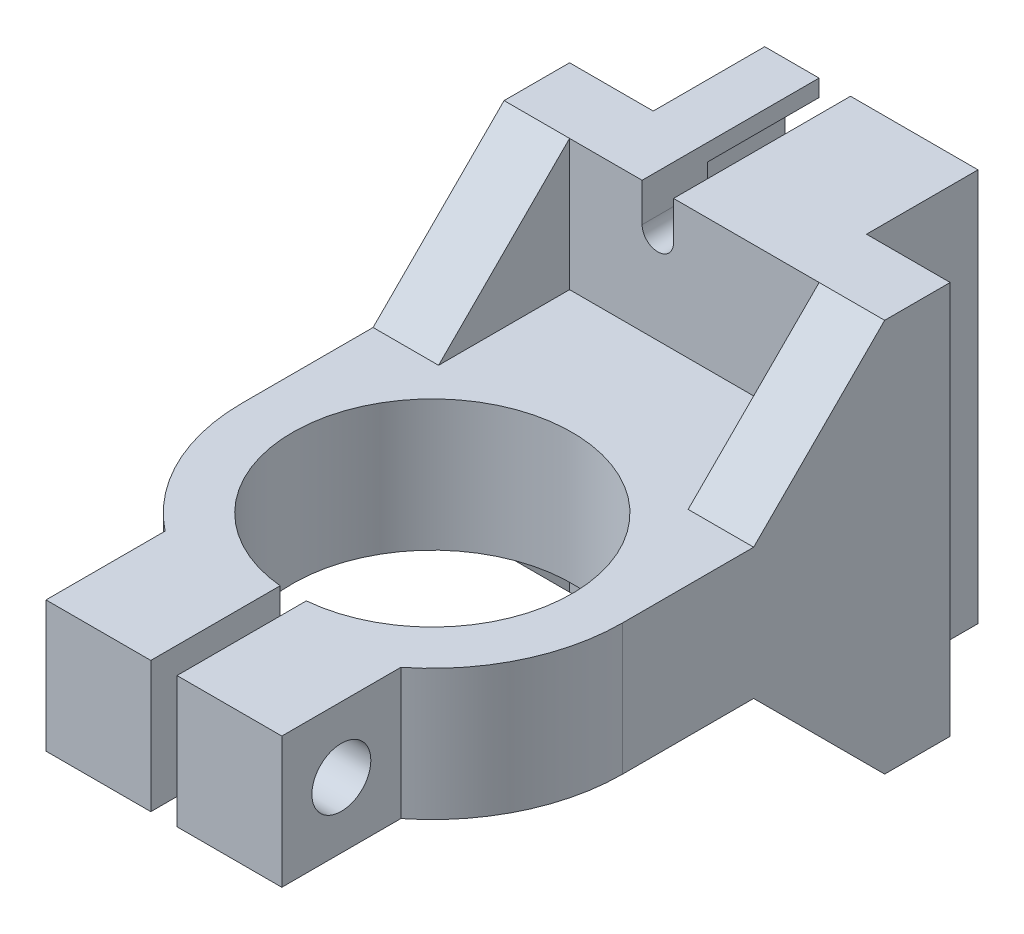
SolidWorks part; units mm, degrees
material "ABS"
ref_plane "Alzado" through (0, 0, 0) normal (0, 0, 1) x (1, 0, 0)
ref_plane "Planta" through (0, 0, 0) normal (0, 1, 0) x (1, 0, 0)
ref_plane "Vista lateral" through (0, 0, 0) normal (1, 0, 0) x (0, 0, -1)
sketch "Croquis1" plane through (0, 0, 0) normal (0, 1, 0) x (1, 0, 0)
  line L0 (0, 0) -> (0, -25) construction
  line L1 (14.525, 0) -> (-14.525, 0)
  line L2 (-14.525, 0) -> (-14.525, -10)
  line L3 (-14.525, -10) -> (-5, -10)
  line L4 (-5, -10) -> (-5, -11.3627)
  line L5 (14.525, 0) -> (14.525, -10)
  line L6 (14.525, -10) -> (5, -10)
  line L7 (5, -10) -> (5, -11.3627)
  arc A0 (-5, -11.3627) -> (5, -11.3627) centre (0, -25) ccw
  circle A1 centre (0, -25) radius 10.668
  point P7 (0, 0)
  dimension "D1" = 29.05
  dimension "D2" = 21.336
  dimension "D3" = 10
  dimension "D4" = 29.05
  dimension "D5" = 25
  dimension "D6" = 5
  dimension "D7" = 10
extrude "Saliente-Extruir1" add sketch "Croquis1" along normal mid plane 10
ref_plane "Plano1" through (0, 0, 39.525) normal (0, 0, 1) x (1, 0, 0)
sketch "Croquis7" plane through (0, 5, 0) normal (0, 1, 0) x (1, 0, 0)
  line L0 (0, -35.668) -> (0, -39.525) construction
  line L2 (1, -41.5965) -> (-1, -41.5965)
  line L3 (1, -41.5965) -> (1, -33.5965)
  line L4 (1, -33.5965) -> (-1, -33.5965)
  line L5 (-1, -41.5965) -> (-1, -33.5965)
  line L6 (1, -41.5965) -> (-1, -33.5965) construction
  line L7 (1, -33.5965) -> (-1, -41.5965) construction
  circle A0 centre (0, -25) radius 10.668 construction
  arc A1 (-5, -11.3627) -> (5, -11.3627) centre (0, -25) ccw construction
  point P7 (0, -37.5965)
  dimension "D1" = 2
  dimension "D2" = 8
extrude "Cortar-Extruir5" cut sketch "Croquis7" against normal through all
sketch "Croquis8" plane through (0, 5, 0) normal (0, 1, 0) x (1, 0, 0)
  line L0 (-1, -39.4905) -> (-1, -45.4905)
  line L1 (-1, -45.4905) -> (-9, -45.4905)
  line L2 (-9, -45.4905) -> (-9, -36.4007)
  line L3 (0, -16.5) -> (0, 16.5) construction
  line L4 (9, -45.4905) -> (9, -36.4007)
  line L5 (1, -45.4905) -> (9, -45.4905)
  line L6 (1, -39.4905) -> (1, -45.4905)
  arc A0 (-5, -11.3627) -> (-1, -39.4905) centre (0, -25) ccw construction
  arc A1 (-9, -36.4007) -> (-1, -39.4905) centre (0, -25) ccw
  arc A2 (9, -36.4007) -> (1, -39.4905) centre (0, -25) cw
  dimension "D1" = 8
  dimension "D2" = 6
extrude "Saliente-Extruir3" add sketch "Croquis8" against normal up to surface (10 mm away) up to face at (0, -5, 16.2414)
sketch "Croquis9" plane through (9, 0, 0) normal (1, 0, 0) x (0, 0, -1)
  line L0 (-40.9456, 5) -> (-40.9456, -5) construction
  line L1 (-45.4905, 5) -> (-36.4007, 5) construction
  line L2 (-36.4007, -5) -> (-45.4905, -5) construction
  circle A0 centre (-40.9456, 0) radius 2.25
  dimension "D1" = 4.5
extrude "Cortar-Extruir6" cut sketch "Croquis9" against normal up to surface (18 mm away) up to face at (-9, 0, 40.9456)
sketch "Croquis10" plane through (0, 5, 0) normal (0, 1, 0) x (1, 0, 0)
  line L0 (-14.525, -10) -> (-14.525, -25)
  line L1 (-5, -10) -> (-5, -11.3627) construction
  line L2 (-14.525, -10) -> (-5, -10) construction
  line L3 (-5, -10) -> (-5, -11.3627)
  line L4 (-14.525, -10) -> (-5, -10)
  line L5 (0, -16.5) -> (0, 16.5) construction
  line L6 (14.525, -10) -> (5, -10)
  line L7 (14.525, -10) -> (14.525, -25)
  line L8 (5, -10) -> (5, -11.3627)
  arc A0 (-5, -11.3627) -> (-9, -36.4007) centre (0, -25) ccw construction
  arc A1 (-5, -11.3627) -> (-14.525, -25) centre (0, -25) ccw
  arc A2 (5, -11.3627) -> (14.525, -25) centre (0, -25) cw
extrude "Saliente-Extruir4" add sketch "Croquis10" against normal up to surface (10 mm away)
sketch "Croquis11" plane through (0, 0, 0) normal (0, 0, -1) x (-1, 0, 0)
  line L0 (-14.525, 5) -> (-14.525, 15)
  line L1 (-14.525, 15) -> (14.525, 15)
  line L2 (14.525, 15) -> (14.525, 5)
  line L3 (14.525, 5) -> (-14.525, 5)
  point P6 (-12.1844, 15)
  dimension "D1" = 10
extrude "Saliente-Extruir5" add sketch "Croquis11" against normal blind 5
sketch "Croquis13" plane through (0, 0, 0) normal (0, 0, -1) x (-1, 0, 0)
  line L0 (0, 0) -> (2.79, 0) construction
  line L1 (2.79, 0) -> (2.79, 12.065) construction
  line L2 (1.59, 12.065) -> (1.59, 15)
  line L3 (14.525, 15) -> (-14.525, 15) construction
  line L4 (1.59, 15) -> (3.99, 15)
  line L5 (3.99, 15) -> (3.99, 12.065)
  arc A0 (1.59, 12.065) -> (3.99, 12.065) centre (2.79, 12.065) ccw
  dimension "D3" = 2.935
  dimension "D1" = 2.79
  dimension "D2" = 2.4
extrude "Cortar-Extruir7" cut sketch "Croquis13" against normal up to next
mirror "Simetría1" about plane through (0, 0, 0) normal (0, 1, 0) of "Cortar-Extruir7", "Saliente-Extruir5"
sketch "Croquis14" plane through (0, 0, 0) normal (0, 0, -1) x (-1, 0, 0)
  line L0 (1.59, 15) -> (-14.525, 15) construction
  line L1 (-6.6, -13.71) -> (6.6, -13.71)
  line L2 (-6.6, -13.71) -> (-6.6, 13.71)
  line L3 (-6.6, 13.71) -> (6.6, 13.71)
  line L4 (6.6, -13.71) -> (6.6, 13.71)
  line L5 (-6.6, -13.71) -> (6.6, 13.71) construction
  line L6 (-6.6, 13.71) -> (6.6, -13.71) construction
  line L7 (8.14, -15) -> (-8.14, -15)
  line L8 (8.14, -15) -> (8.14, 15)
  line L9 (8.14, 15) -> (-8.14, 15)
  line L10 (-8.14, -15) -> (-8.14, 15)
  line L11 (8.14, -15) -> (-8.14, 15) construction
  line L12 (8.14, 15) -> (-8.14, -15) construction
  line L13 (3.99, 12.065) -> (3.99, 15) construction
  line L14 (1.59, 15) -> (1.59, 12.065) construction
  line L15 (3.99, 12.065) -> (3.99, 15)
  line L16 (1.59, 15) -> (1.59, 12.065)
  line L17 (3.99, -12.065) -> (3.99, -15) construction
  line L18 (1.59, -15) -> (1.59, -12.065) construction
  line L19 (3.99, -12.065) -> (3.99, -15)
  line L20 (1.59, -15) -> (1.59, -12.065)
  arc A0 (1.59, 12.065) -> (3.99, 12.065) centre (2.79, 12.065) ccw construction
  arc A1 (1.59, 12.065) -> (3.99, 12.065) centre (2.79, 12.065) ccw
  arc A2 (3.99, -12.065) -> (1.59, -12.065) centre (2.79, -12.065) ccw construction
  arc A3 (3.99, -12.065) -> (1.59, -12.065) centre (2.79, -12.065) ccw
  point P0 (0, 0)
  point P6 (0, 0)
  line M9 (3.99, -12.065) -> (3.99, -15)
  line M10 (3.99, -15) -> (14.525, -15)
  line M12 (14.525, 15) -> (3.99, 15)
  line M13 (3.99, 15) -> (3.99, 12.065)
  line M15 (1.59, 12.065) -> (1.59, 15)
  line M16 (1.59, 15) -> (-14.525, 15)
  line M18 (-14.525, -15) -> (1.59, -15)
  line M19 (1.59, -15) -> (1.59, -12.065)
  dimension "D1" = 13.2
  dimension "D2" = 27.42
  dimension "D3" = 1.54
extrude "Saliente-Extruir6" add sketch "Croquis14" along normal blind 8.51 contours L10 L1 L2 L3 M18 M19 M15 M16 | L8 L3 L4 L1 M10 M12 M13 M9
sketch "Croquis15" plane through (0, -15, 0) normal (0, -1, 0) x (1, 0, 0)
  line L6 (-8.14, -8.51) -> (-8.14, 0) construction
  line L7 (4.29, -3.61) -> (4.29, -8.51)
  line L8 (8.14, -8.51) -> (-1.59, -8.51) construction
  line L9 (1.53, -0.85) -> (-1.59, -0.85)
  line L10 (-1.59, 5) -> (-1.59, -8.51) construction
  line L11 (-1.59, -0.85) -> (-1.59, -8.51)
  line L12 (-1.59, -8.51) -> (4.29, -8.51)
  line L13 (8.14, -8.51) -> (8.14, 0) construction
  line L15 (8.14, 0) -> (14.525, 0) construction
  arc A1 (4.29, -3.61) -> (1.53, -0.85) centre (1.53, -3.61) ccw
  point P15 (1.53, -0.7274)
  point P16 (-1.59, -0.9355)
  dimension "D1" = 9.67
  dimension "D2" = 3.85
  dimension "D3" = 0.85
extrude "Cortar-Extruir8" cut sketch "Croquis15" against normal up to next
sketch "Croquis16" plane through (-14.525, 0, 0) normal (-1, 0, 0) x (0, 0, 1)
  line L0 (5, 15) -> (15, 5)
  line L1 (5, 5) -> (25, 5) construction
  line L2 (15, 5) -> (5, 5)
  line L3 (5, 5) -> (5, 15)
  line L4 (15.9775, 0) -> (-15.9775, 0) construction
  line L5 (15, -5) -> (5, -5)
  line L6 (5, -15) -> (15, -5)
  line L7 (5, -5) -> (5, -15)
  line L8 (5, -5) -> (5, -15) construction
  point P14 (5, -15)
  dimension "D1" = 10
extrude "Saliente-Extruir7" add sketch "Croquis16" against normal blind 5
mirror "Simetría2" about plane through (0, 0, 0) normal (1, 0, 0) of "Saliente-Extruir7"
